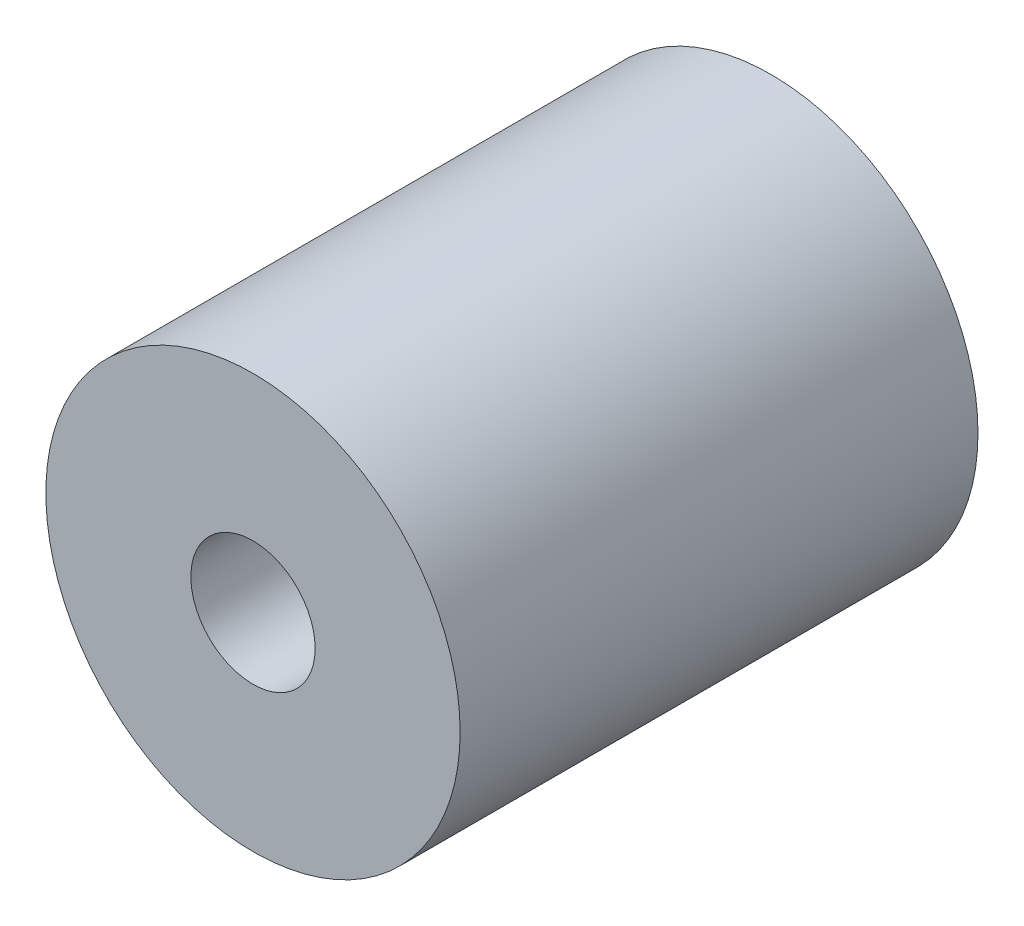
SolidWorks part; units mm, degrees
material "1060 Alloy"
ref_plane "Front Plane" through (0, 0, 0) normal (0, 0, 1) x (1, 0, 0)
ref_plane "Top Plane" through (0, 0, 0) normal (0, 1, 0) x (1, 0, 0)
ref_plane "Right Plane" through (0, 0, 0) normal (1, 0, 0) x (0, 0, -1)
sketch "Sketch1" plane through (0, 0, 0) normal (0, 0, 1) x (1, 0, 0)
  circle A0 centre (0, 0) radius 10
extrude "Boss-Extrude1" add sketch "Sketch1" along normal blind 25
sketch "Sketch2" plane through (0, 0, 25) normal (0, 0, 1) x (1, 0, 0)
  circle A0 centre (0, 0) radius 3
extrude "Cut-Extrude1" cut sketch "Sketch2" against normal blind 12
sketch "Sketch3" plane through (0, 0, 0) normal (0, 0, -1) x (-1, 0, 0)
  circle A0 centre (0, 0) radius 4
extrude "Cut-Extrude2" cut sketch "Sketch3" against normal blind 12
